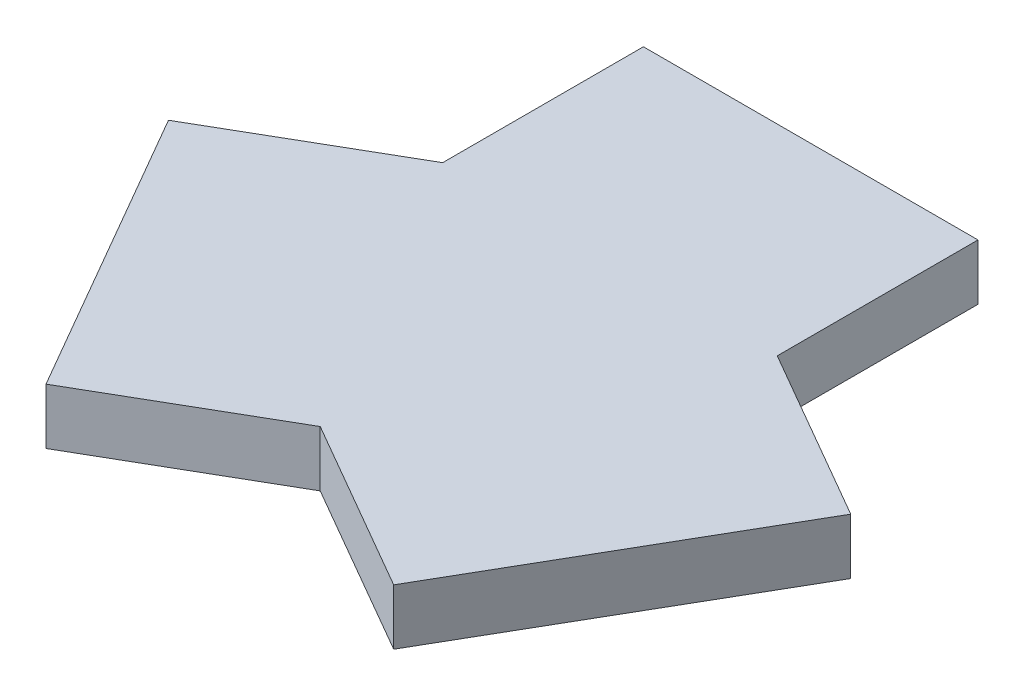
SolidWorks part; units mm, degrees
ref_plane "Front Plane" through (0, 0, 0) normal (0, 0, 1) x (1, 0, 0)
ref_plane "Top Plane" through (0, 0, 0) normal (0, 1, 0) x (1, 0, 0)
ref_plane "Right Plane" through (0, 0, 0) normal (1, 0, 0) x (0, 0, -1)
sketch "Sketch1" plane through (0, 0, 0) normal (0, 1, 0) x (1, 0, 0)
  line L0 (15.2942, 0.5) -> (7.5, 5)
  line L1 (7.5, 5) -> (7.5, 14)
  line L5 (0, -7.9904) -> (7.7942, -12.4904)
  line L7 (7.5, 5) -> (0, -7.9904) construction
  line L8 (7.5, 5) -> (-7.5, 5) construction
  line L9 (-7.5, 14) -> (7.5, 14)
  line L10 (15.2942, 0.5) -> (7.7942, -12.4904)
  line L12 (0, 30.0328) -> (0, -20.7177) construction
  line L13 (-7.5, 5) -> (0, -7.9904) construction
  line L14 (-15.2942, 0.5) -> (-7.7942, -12.4904)
  line L15 (0, -7.9904) -> (-7.7942, -12.4904)
  line L16 (-15.2942, 0.5) -> (-7.5, 5)
  line L17 (-7.5, 5) -> (-7.5, 14)
  point P6 (0, 5)
  point P9 (0, 14)
  dimension "D3" = 15
  dimension "D4" = 9
  dimension "D5" = 9
extrude "Boss-Extrude1" add sketch "Sketch1" along normal mid plane 2.5
